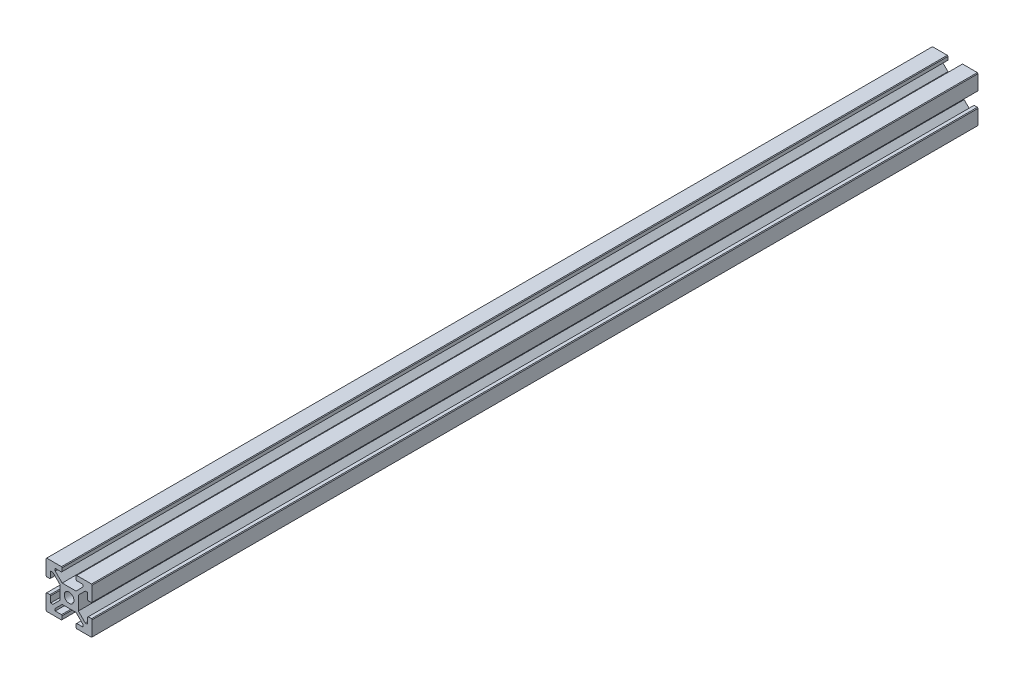
SolidWorks part; units mm, degrees
ref_plane "Front" through (0, 0, 0) normal (0, 0, 1) x (1, 0, 0)
ref_plane "Top" through (0, 0, 0) normal (0, 1, 0) x (1, 0, 0)
ref_plane "Right" through (0, 0, 0) normal (1, 0, 0) x (0, 0, -1)
sketch "Sketch1" plane through (0, 0, 0) normal (0, 0, 1) x (1, 0, 0)
  line L0 (-3, 10) -> (3, 10)
  line L1 (-10, 10) -> (10, 10)
  line L2 (-10, 10) -> (-10, -10)
  line L3 (-10, -10) -> (10, -10)
  line L4 (10, 10) -> (10, -10)
  line L5 (-10, 10) -> (10, -10) construction
  line L6 (-10, -10) -> (10, 10) construction
  line L7 (3, 10) -> (3, 8)
  line L8 (3, 8) -> (6, 8)
  line L9 (-3, 4) -> (3, 4)
  line L10 (0, -11) -> (0, 11) construction
  line L11 (3, 4) -> (6, 7)
  line L12 (6, 7) -> (6, 8)
  line L13 (10, 3) -> (10, -3)
  line L14 (-3, 10) -> (-3, 8)
  line L15 (-3, 8) -> (-6, 8)
  line L16 (-6, 7) -> (-6, 8)
  line L17 (-3, 4) -> (-6, 7)
  line L18 (10, -3) -> (8, -3)
  line L19 (8, -3) -> (8, -6)
  line L20 (7, -6) -> (8, -6)
  line L21 (4, -3) -> (7, -6)
  line L22 (4, 3) -> (4, -3)
  line L23 (4, 3) -> (7, 6)
  line L24 (7, 6) -> (8, 6)
  line L25 (8, 3) -> (8, 6)
  line L26 (10, 3) -> (8, 3)
  line L27 (3, -10) -> (-3, -10)
  line L28 (-3, -10) -> (-3, -8)
  line L29 (-3, -8) -> (-6, -8)
  line L30 (-6, -7) -> (-6, -8)
  line L31 (-3, -4) -> (-6, -7)
  line L32 (3, -4) -> (-3, -4)
  line L33 (3, -4) -> (6, -7)
  line L34 (6, -7) -> (6, -8)
  line L35 (3, -8) -> (6, -8)
  line L36 (3, -10) -> (3, -8)
  line L37 (-10, -3) -> (-10, 3)
  line L38 (-10, 3) -> (-8, 3)
  line L39 (-8, 3) -> (-8, 6)
  line L40 (-7, 6) -> (-8, 6)
  line L41 (-4, 3) -> (-7, 6)
  line L42 (-4, -3) -> (-4, 3)
  line L43 (-4, -3) -> (-7, -6)
  line L44 (-7, -6) -> (-8, -6)
  line L45 (-8, -3) -> (-8, -6)
  line L46 (-10, -3) -> (-8, -3)
  circle A0 centre (0, 0) radius 2.1
  point P0 (0, 0)
  point P18 (0, 10)
  point P22 (0, 4)
  point P53 (0, 0)
  dimension "D1" = 20
  dimension "D2" = 20
  dimension "D3" = 3
  dimension "D4" = 2
  dimension "D5" = 3
  dimension "D6" = 6
  dimension "D7" = 3
  dimension "D8" = 4
extrude "Boss-Extrude1" add sketch "Sketch1" along normal blind 383.54 contours L46 L2 L3 L28 L29 L30 L31 L32 L33 L34 L35 L36 L4 L18 L19 L20 L21 L22 L23 L24 L25 L26 L1 L7 L8 L12 L11 L9 L17 L16 L15 L14 L38 L39 L40 L41 L42 L43 L44 L45 A0
chamfer "Chamfer1" distance 0.2828 angle 45 20 edges at (-8, 3, 191.77) (-3, 8, 191.77) (-3, 10, 191.77) (-10, 3, 191.77) (-10, 10, 191.77) (-8, -3, 191.77) (-10, -3, 191.77) (-10, -10, 191.77) (-3, -10, 191.77) (-3, -8, 191.77) (3, -8, 191.77) (3, -10, 191.77) (8, -3, 191.77) (10, -10, 191.77) (10, -3, 191.77) (8, 3, 191.77) (10, 3, 191.77) (10, 10, 191.77) (3, 8, 191.77) (3, 10, 191.77)
